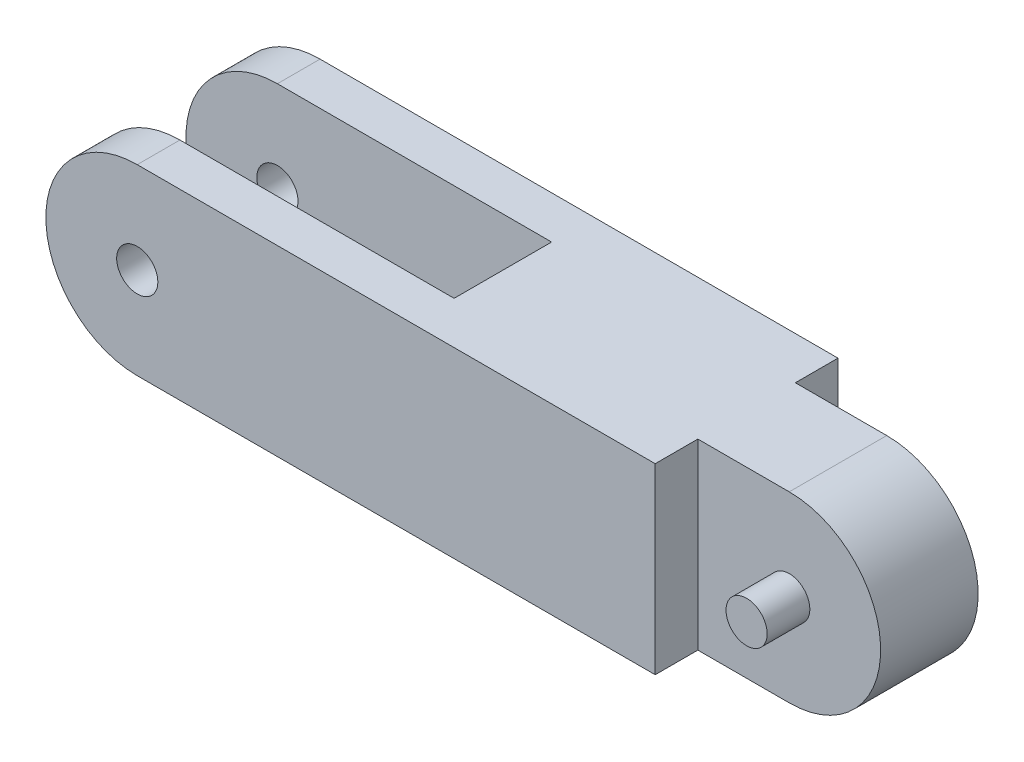
SolidWorks part; units mm, degrees
material "1060 Alloy"
ref_plane "Front Plane" through (0, 0, 0) normal (0, 0, 1) x (1, 0, 0)
ref_plane "Top Plane" through (0, 0, 0) normal (0, 1, 0) x (1, 0, 0)
ref_plane "Right Plane" through (0, 0, 0) normal (1, 0, 0) x (0, 0, -1)
sketch "Sketch1" plane through (0, 0, 0) normal (0, 0, 1) x (1, 0, 0)
  line L0 (-50, 0) -> (50, 0) construction
  line L1 (-50, 15) -> (50, 15)
  line L2 (-50, -15) -> (50, -15)
  arc A0 (-50, 15) -> (-50, -15) centre (-50, 0) ccw
  arc A1 (50, -15) -> (50, 15) centre (50, 0) ccw
  point P2 (0, 0)
  dimension "D1" = 100
  dimension "D2" = 30
extrude "Boss-Extrude1" add sketch "Sketch1" along normal mid plane 30
hole_wizard "H (0.266) Diameter Hole1" positions "Sketch2" profile "Sketch4" hole size "H" standard "ANSI Inch" end condition through all
sketch "Sketch2" plane through (0, 0, 15) normal (0, 0, 1) x (1, 0, 0)
  point P0 (-50, 0)
  point P3 (50, 0)
sketch "Sketch4" plane through (-50, 0, 15) normal (1, 0, 0) x (0, -1, 0)
  line L0 (0, 0) -> (0, 30)
  line L1 (0, 30) -> (3.3782, 30)
  line L2 (3.3782, 30) -> (3.3782, 0)
  line L5 (3.3782, 0) -> (0, 0)
  line L11 (0, -6.35) -> (0, 107.95) construction
  dimension "Thru Hole Dia." = 6.7564
  dimension "Thru Hole Depth" = 30
sketch "Sketch5" plane through (0, 15, 0) normal (0, 1, 0) x (1, 0, 0)
  line L1 (-65, 8) -> (-5, 8)
  line L2 (-65, 8) -> (-65, -8)
  line L3 (-65, -8) -> (-5, -8)
  line L4 (-5, 8) -> (-5, -8)
  line L5 (-5, 0) -> (0, 0) construction
  line L6 (-50, -15) -> (-50, 15) construction
  line L7 (50, -15) -> (50, 15) construction
  line L8 (35, 28.9161) -> (95, 28.9161)
  line L9 (35, 28.9161) -> (35, 8)
  line L10 (35, 8) -> (95, 8)
  line L11 (95, 28.9161) -> (95, 8)
  line L12 (35, -28.9161) -> (95, -28.9161)
  line L13 (35, -28.9161) -> (35, -8)
  line L14 (35, -8) -> (95, -8)
  line L15 (95, -28.9161) -> (95, -8)
  dimension "D1" = 16
  dimension "D2" = 45
  dimension "D3" = 60
  dimension "D4" = 15
extrude "Cut-Extrude1" cut sketch "Sketch5" against normal through all
sketch "Sketch6" plane through (0, 0, 0) normal (0, 0, 1) x (1, 0, 0)
  circle A0 centre (50, 0) radius 3.3782
extrude "Boss-Extrude2" add sketch "Sketch6" along normal up to surface and the other way up to surface up to face at (-11.25, 0, 15) other way up to face at (-46.6218, 0, -15)
